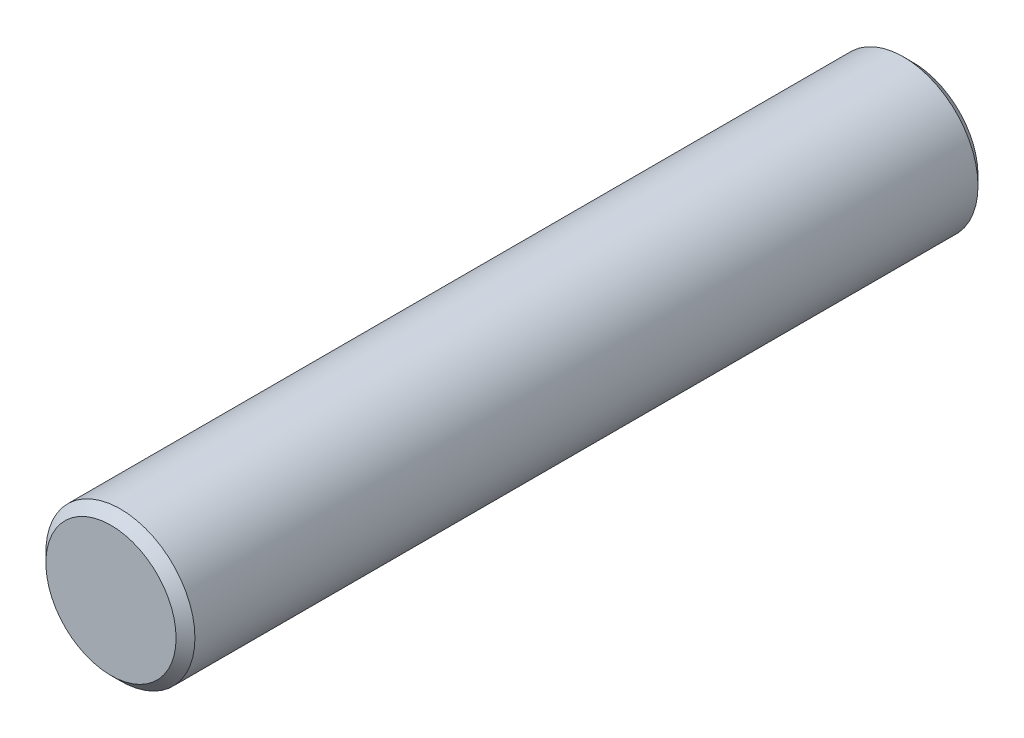
SolidWorks part; units mm, degrees
ref_plane "Plane1" through (0, 0, 0) normal (0, 0, 1) x (1, 0, 0)
ref_plane "Plane2" through (0, 0, 0) normal (0, 1, 0) x (1, 0, 0)
ref_plane "Plane3" through (0, 0, 0) normal (1, 0, 0) x (0, 0, -1)
sketch "Sketch1" plane through (0, 0, 0) normal (0, 0, 1) x (1, 0, 0)
  circle A0 centre (0, 0) radius 0.79
  dimension "D1" = 1.58
extrude "drive shaft pin shape" add sketch "Sketch1" along normal blind 8.5
chamfer "drive shaft pin chamfer" distance 0.1 angle 45 2 edges at (0.79, 0, 0) (0.79, 0, 8.5)
